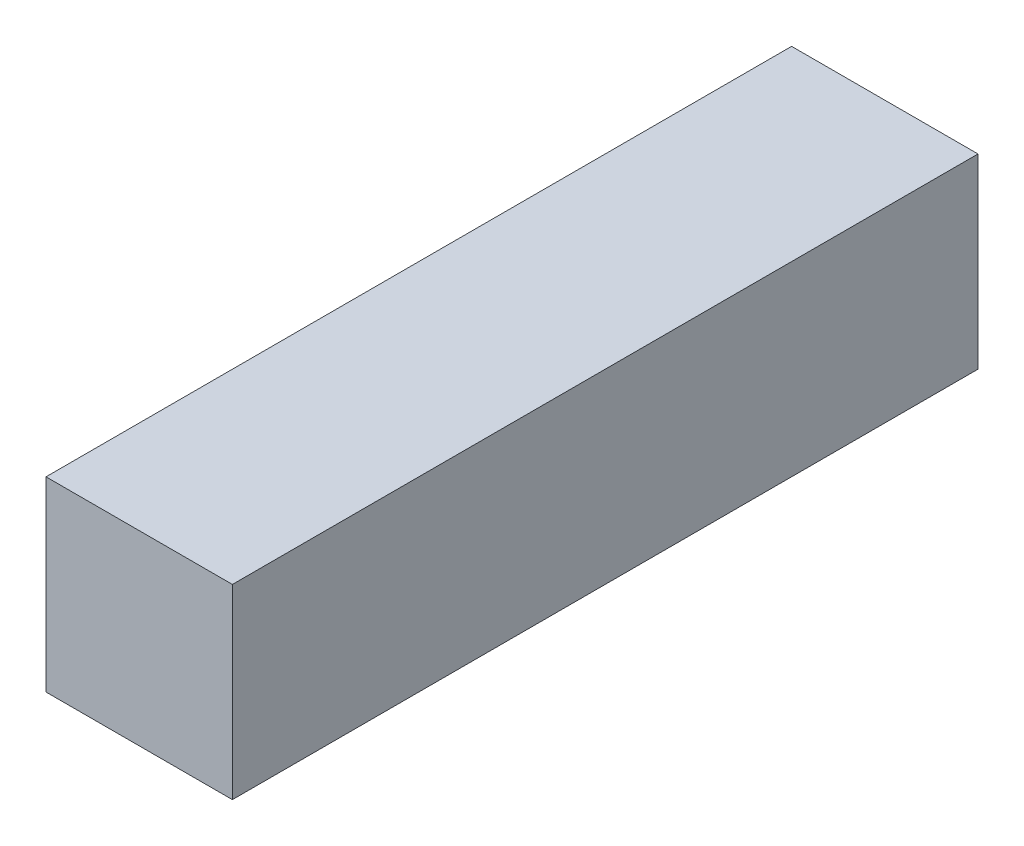
SolidWorks part; units mm, degrees
ref_plane "Plan de face" through (0, 0, 0) normal (0, 0, 1) x (1, 0, 0)
ref_plane "Plan de dessus" through (0, 0, 0) normal (0, 1, 0) x (1, 0, 0)
ref_plane "Plan de droite" through (0, 0, 0) normal (1, 0, 0) x (0, 0, -1)
sketch "Esquisse1" plane through (0, 0, 0) normal (0, 0, 1) x (1, 0, 0)
  line L1 (0, 0) -> (100, 0)
  line L2 (0, 0) -> (0, 100)
  line L3 (0, 100) -> (100, 100)
  line L4 (100, 0) -> (100, 100)
  dimension "D1" = 100
  dimension "D2" = 100
extrude "Boss.-Extru.1" add sketch "Esquisse1" along normal blind 400
